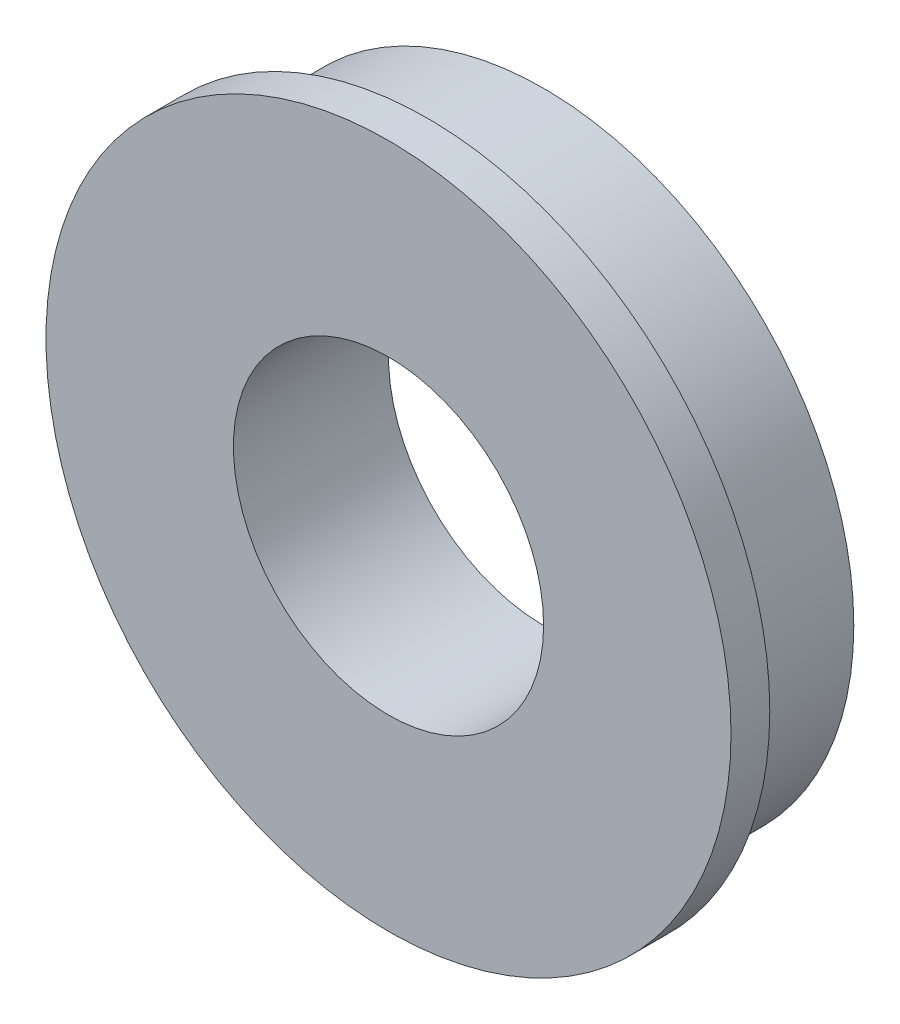
SolidWorks part; units mm, degrees
material "ｽﾃﾝﾚｽ鋼(ｸﾛﾑ)"
ref_plane "正面" through (0, 0, 0) normal (0, 0, 1) x (1, 0, 0)
ref_plane "平面" through (0, 0, 0) normal (0, 1, 0) x (1, 0, 0)
ref_plane "右側面" through (0, 0, 0) normal (1, 0, 0) x (0, 0, -1)
sketch "ｽｹｯﾁ1" plane through (0, 0, 0) normal (0, 0, 1) x (1, 0, 0)
  circle A0 centre (0, 0) radius 12
  dimension "D1" = 24
extrude "押し出し1" add sketch "ｽｹｯﾁ1" against normal blind 4.5
sketch "ｽｹｯﾁ2" plane through (0, 0, 0) normal (0, 0, 1) x (1, 0, 0)
  circle A0 centre (0, 0) radius 13.25
  dimension "D1" = 26.5
extrude "押し出し2" add sketch "ｽｹｯﾁ2" along normal blind 1.5
sketch "ｽｹｯﾁ3" plane through (0, 0, 1.5) normal (0, 0, 1) x (1, 0, 0)
  circle A0 centre (0, 0) radius 6
  dimension "D1" = 12
extrude "ｶｯﾄ - 押し出し1" cut sketch "ｽｹｯﾁ3" against normal through all
